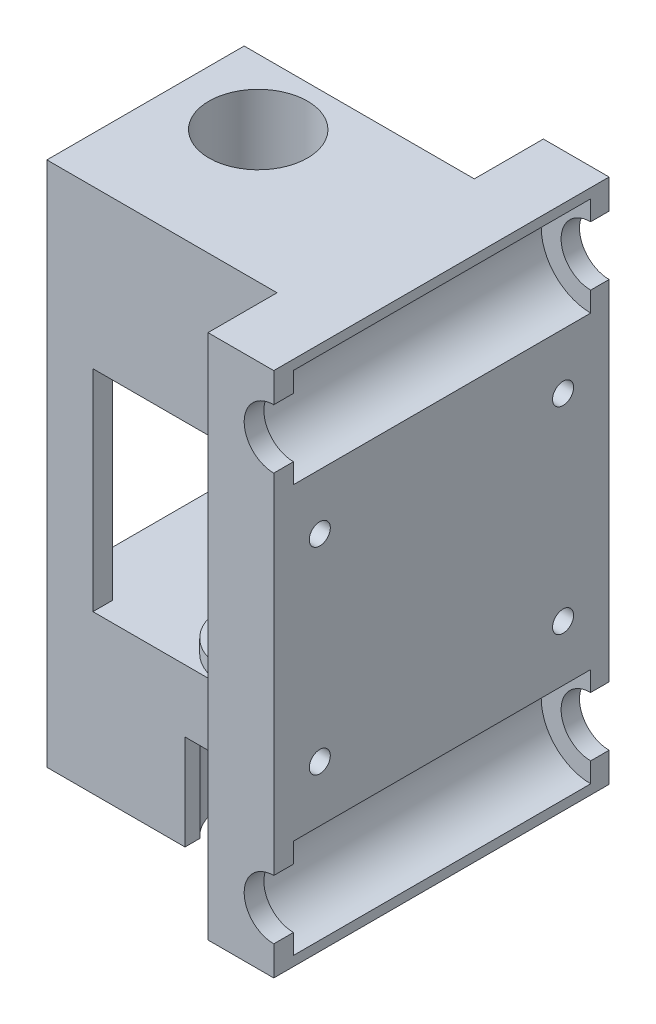
SolidWorks part; units mm, degrees
ref_plane "Front Plane" through (0, 0, 0) normal (0, 0, 1) x (1, 0, 0)
ref_plane "Top Plane" through (0, 0, 0) normal (0, 1, 0) x (1, 0, 0)
ref_plane "Right Plane" through (0, 0, 0) normal (1, 0, 0) x (0, 0, -1)
sketch "Sketch1" plane through (0, 0, 0) normal (0, 0, 1) x (1, 0, 0)
  line L1 (0, 0) -> (-10, 0)
  line L2 (0, 0) -> (0, 80)
  line L3 (0, 80) -> (-10, 80)
  line L4 (-10, 0) -> (-10, 80)
  dimension "D1" = 10
  dimension "D2" = 80
extrude "Boss-Extrude1" add sketch "Sketch1" along normal blind 51
ref_plane "Plane1" through (0, 0, 48) normal (0, 0, 1) x (1, 0, 0)
sketch "Sketch2" plane through (0, 0, 48) normal (0, 0, 1) x (1, 0, 0)
  line L0 (0, 0) -> (0, 80) construction
  line L1 (0, 80) -> (-10, 80) construction
  line L2 (-10, 0) -> (0, 0) construction
  circle A0 centre (0, 71) radius 7.525
  circle A1 centre (0, 9) radius 7.525
  dimension "D1" = 15.05
  dimension "D2" = 15.05
  dimension "D3" = 9
  dimension "D4" = 9
extrude "Cut-Extrude1" cut sketch "Sketch2" against normal blind 45.2
sketch "Sketch3" plane through (0, 0, 51) normal (0, 0, 1) x (1, 0, 0)
  line L0 (0, 0) -> (0, 80) construction
  circle A0 centre (0, 71) radius 4.5
  circle A1 centre (0, 9) radius 4.5
  arc A2 (0, 16.525) -> (0, 1.475) centre (0, 9) ccw construction
  arc A3 (0, 78.525) -> (0, 63.475) centre (0, 71) ccw construction
  dimension "D1" = 9
extrude "Cut-Extrude2" cut sketch "Sketch3" against normal through all
sketch "Sketch4" plane through (-10, 0, 0) normal (-1, 0, 0) x (0, 0, 1)
  line L0 (51, 0) -> (0, 0) construction
  line L1 (10.5, 0) -> (40.5, 0)
  line L2 (10.5, 0) -> (10.5, 80)
  line L3 (10.5, 80) -> (40.5, 80)
  line L4 (40.5, 0) -> (40.5, 80)
  line L5 (51, 80) -> (0, 80) construction
  line L6 (25.5, 0) -> (25.5, 18.6852) construction
  point P10 (25.5, 80)
  dimension "D1" = 30
extrude "Boss-Extrude2" add sketch "Sketch4" along normal blind 35
sketch "Sketch6" plane through (-45, 0, 0) normal (-1, 0, 0) x (0, 0, 1)
  line L0 (40.5, 80) -> (10.5, 80) construction
  line L1 (10.5, 0) -> (40.5, 0) construction
  line L2 (25.5, 80) -> (25.5, 46.5373) construction
  circle A0 centre (25.5, 71) radius 4.015
  circle A1 centre (25.5, 9) radius 4.015
  dimension "D3" = 8.03
  dimension "D1" = 9
  dimension "D2" = 9
extrude "Cut-Extrude3" cut sketch "Sketch6" against normal blind 5
sketch "Sketch7" plane through (-45, 0, 0) normal (-1, 0, 0) x (0, 0, 1)
  line L0 (10.5, 80) -> (10.5, 0) construction
  line L1 (13.5, 24) -> (37.5, 24)
  line L2 (13.5, 24) -> (13.5, 56)
  line L3 (13.5, 56) -> (37.5, 56)
  line L4 (37.5, 24) -> (37.5, 56)
  line L5 (40.5, 0) -> (40.5, 80) construction
  line L8 (10.5, 40) -> (40.5, 40) construction
  point P10 (13.5, 40)
  dimension "D1" = 3
  dimension "D2" = 3
  dimension "D3" = 32
extrude "Cut-Extrude4" cut sketch "Sketch7" against normal up to surface (35 mm away) up to face at (-10, 40, 5.25)
sketch "Sketch8" plane through (0, 0, 40.5) normal (0, 0, 1) x (1, 0, 0)
  line L0 (-10, 80) -> (-10, 0) construction
  line L1 (-38, 24) -> (-10, 24)
  line L2 (-38, 24) -> (-38, 56)
  line L3 (-38, 56) -> (-10, 56)
  line L4 (-10, 24) -> (-10, 56)
  line L5 (-45, 40) -> (-36.5609, 40) construction
  line L6 (-45, 0) -> (-45, 80) construction
  point P9 (-38, 40)
  dimension "D1" = 7
  dimension "D2" = 32
extrude "Cut-Extrude5" cut sketch "Sketch8" against normal through all
sketch "Sketch14" plane through (-10, 0, 0) normal (-1, 0, 0) x (0, 0, 1)
  line L0 (0, 80) -> (0, 0) construction
  line L1 (47.262, 55) -> (45.631, 57.825)
  line L2 (45.631, 57.825) -> (42.369, 57.825)
  line L3 (42.369, 57.825) -> (40.738, 55)
  line L4 (40.738, 55) -> (42.369, 52.175)
  line L5 (42.369, 52.175) -> (45.631, 52.175)
  line L6 (45.631, 52.175) -> (47.262, 55)
  line L7 (10.262, 55) -> (8.631, 57.825)
  line L8 (8.631, 57.825) -> (5.369, 57.825)
  line L9 (5.369, 57.825) -> (3.738, 55)
  line L10 (3.738, 55) -> (5.369, 52.175)
  line L11 (5.369, 52.175) -> (8.631, 52.175)
  line L12 (8.631, 52.175) -> (10.262, 55)
  line L13 (10.262, 25) -> (8.631, 27.825)
  line L14 (8.631, 27.825) -> (5.369, 27.825)
  line L15 (5.369, 27.825) -> (3.738, 25)
  line L16 (3.738, 25) -> (5.369, 22.175)
  line L17 (5.369, 22.175) -> (8.631, 22.175)
  line L18 (8.631, 22.175) -> (10.262, 25)
  line L19 (47.262, 25) -> (45.631, 27.825)
  line L20 (45.631, 27.825) -> (42.369, 27.825)
  line L21 (42.369, 27.825) -> (40.738, 25)
  line L22 (40.738, 25) -> (42.369, 22.175)
  line L23 (42.369, 22.175) -> (45.631, 22.175)
  line L24 (45.631, 22.175) -> (47.262, 25)
  line L25 (51, 80) -> (51, 0) construction
  line L26 (51, 80) -> (40.5, 80) construction
  line L27 (51, 0) -> (0, 0) construction
  circle A4 centre (44, 55) radius 2.825 construction
  circle A5 centre (7, 55) radius 2.825 construction
  circle A6 centre (7, 25) radius 2.825 construction
  circle A7 centre (44, 25) radius 2.825 construction
  dimension "D1" = 5.65
  dimension "D2" = 7
  dimension "D3" = 7
  dimension "D4" = 25
  dimension "D5" = 25
extrude "Cut-Extrude9" cut sketch "Sketch14" against normal blind 3
sketch "Sketch15" plane through (-7, 0, 0) normal (-1, 0, 0) x (0, 0, 1)
  line L0 (0, 80) -> (0, 0) construction
  line L1 (51, 80) -> (40.5, 80) construction
  line L2 (51, 80) -> (51, 0) construction
  line L3 (10.5, 0) -> (40.5, 0) construction
  circle A0 centre (44, 55) radius 1.6
  circle A1 centre (7, 55) radius 1.6
  circle A2 centre (7, 25) radius 1.6
  circle A3 centre (44, 25) radius 1.6
  dimension "D1" = 3.2
  dimension "D2" = 7
  dimension "D3" = 25
  dimension "D4" = 7
  dimension "D5" = 25
extrude "Cut-Extrude10" cut sketch "Sketch15" against normal through all
sketch "Sketch16" plane through (0, 80, 0) normal (0, 1, 0) x (1, 0, 0)
  line L0 (-45, -40.5) -> (-45, -10.5) construction
  line L1 (-45, -40.5) -> (-10, -40.5) construction
  circle A0 centre (-19, -32.664) radius 4
  dimension "D1" = 8
  dimension "D2" = 26
  dimension "D3" = 7.836
extrude "Cut-Extrude11" cut sketch "Sketch16" against normal through all
sketch "Sketch19" plane through (0, 0, 0) normal (0, -1, 0) x (1, 0, 0)
  line L0 (-45, 10.5) -> (-10, 10.5) construction
  line L1 (-45, 10.5) -> (-45, 40.5) construction
  circle A0 centre (-32.925, 20.436) radius 4
  dimension "D1" = 8
  dimension "D2" = 9.936
  dimension "D3" = 12.075
extrude "Cut-Extrude13" cut sketch "Sketch19" against normal through all
sketch "Sketch20" plane through (0, 56, 0) normal (0, -1, 0) x (1, 0, 0)
  circle A0 centre (-32.925, 20.436) radius 7.5
  circle A1 centre (-32.925, 20.436) radius 4 construction
  circle A2 centre (-32.925, 20.436) radius 4
  dimension "D1" = 15
extrude "Boss-Extrude3" add sketch "Sketch20" along normal blind 5.45
sketch "Sketch21" plane through (0, 24, 0) normal (0, 1, 0) x (1, 0, 0)
  circle A0 centre (-19, -32.664) radius 7.5
  circle A1 centre (-19, -32.664) radius 4 construction
  circle A2 centre (-19, -32.664) radius 4
  dimension "D1" = 15
extrude "Boss-Extrude4" add sketch "Sketch21" along normal blind 2.1
sketch "Sketch22" plane through (0, 56, 0) normal (0, -1, 0) x (1, 0, 0)
  circle A0 centre (-19, 32.664) radius 4 construction
  circle A1 centre (-19, 32.664) radius 4
extrude "Boss-Extrude5" add sketch "Sketch22" against normal up to surface (24 mm away) up to face at (-32.925, 80, 16.436)
sketch "Sketch23" plane through (0, 24, 0) normal (0, 1, 0) x (1, 0, 0)
  circle A0 centre (-32.925, -20.436) radius 4 construction
  circle A1 centre (-32.925, -20.436) radius 4
extrude "Boss-Extrude6" add sketch "Sketch23" against normal up to surface (24 mm away) up to face at (-32.925, 0, 16.436)
sketch "Sketch24" plane through (0, 80, 0) normal (0, 1, 0) x (1, 0, 0)
  circle A0 centre (-32.925, -20.436) radius 7.5
  circle A1 centre (-32.925, -20.436) radius 4 construction
  dimension "D1" = 15
extrude "Cut-Extrude14" cut sketch "Sketch24" against normal blind 17.8
sketch "Sketch25" plane through (0, 0, 0) normal (0, -1, 0) x (1, 0, 0)
  circle A0 centre (-19, 32.664) radius 7.5
  circle A1 centre (-19, 32.664) radius 4 construction
  dimension "D1" = 15
extrude "Cut-Extrude15" cut sketch "Sketch25" against normal blind 14.5
sketch "Sketch26" plane through (0, 0, 0) normal (0, -1, 0) x (1, 0, 0)
  line L0 (-14, 40.5) -> (-14, 38.2542)
  line L1 (-24, 40.5) -> (-24, 38.2542)
  line L2 (-19, 32.664) -> (-19, 40.5) construction
  line L8 (-10, 0) -> (0, 0)
  line L9 (0, 0) -> (0, 51)
  line L10 (0, 51) -> (-10, 51)
  line L11 (-10, 51) -> (-10, 40.5)
  line L12 (-10, 40.5) -> (-45, 40.5)
  line L13 (-45, 40.5) -> (-45, 10.5)
  line L14 (-45, 10.5) -> (-10, 10.5)
  line L15 (-10, 10.5) -> (-10, 0)
  line L20 (-14, 40.5) -> (-24, 40.5)
  circle A0 centre (-19, 32.664) radius 7.5 construction
  arc A1 (-14, 38.2542) -> (-24, 38.2542) centre (-19, 32.664) ccw
  dimension "D2" = 10
  dimension "D3" = 5
  dimension "D1" = 0
extrude "Cut-Extrude16" cut sketch "Sketch26" against normal up to surface (14.5 mm away) up to face at (-19, 14.5, 25.164)
